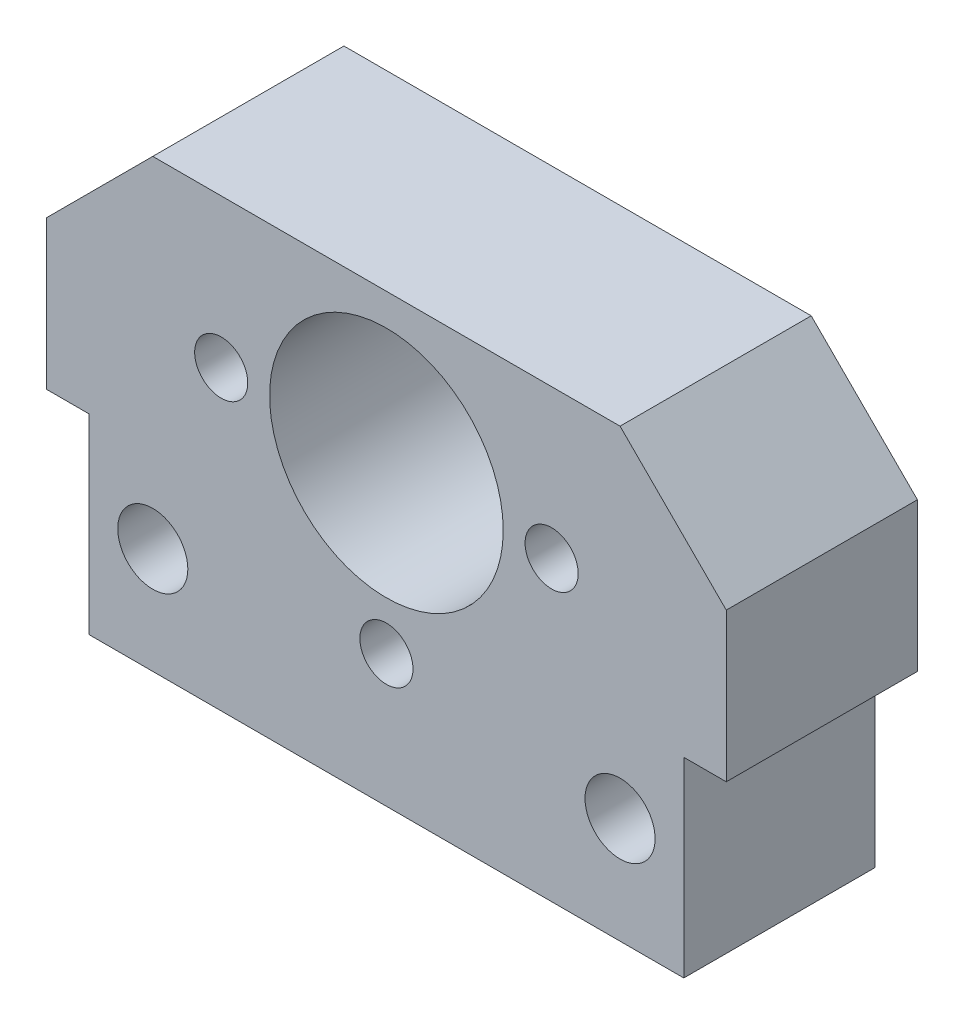
SolidWorks part; units mm, degrees
ref_plane "Plan de face" through (0, 0, 0) normal (0, 0, 1) x (1, 0, 0)
ref_plane "Plan de dessus" through (0, 0, 0) normal (0, 1, 0) x (1, 0, 0)
ref_plane "Plan de droite" through (0, 0, 0) normal (1, 0, 0) x (0, 0, -1)
sketch "Esquisse1" plane through (0, 0, 0) normal (0, 0, 1) x (1, 0, 0)
  line L1 (0, 0) -> (32, 0)
  line L2 (0, 0) -> (0, 19)
  line L3 (0, 19) -> (32, 19)
  line L4 (32, 0) -> (32, 19)
  dimension "D1" = 32
  dimension "D2" = 19
extrude "Boss.-Extru.1" add sketch "Esquisse1" along normal blind 9
sketch "Esquisse2" plane through (0, 0, 9) normal (0, 0, 1) x (1, 0, 0)
  line L0 (16, 12) -> (16, 19) construction
  line L1 (32, 19) -> (0, 19) construction
  line L2 (16, 12) -> (8.2218, 12) construction
  line L3 (16, 4.2218) -> (8.2218, 12) construction
  line L4 (16, 4.2218) -> (23.7782, 12) construction
  line L5 (16, 4.2218) -> (16, 12) construction
  line L6 (0, 0) -> (32, 0) construction
  line L7 (5, 0) -> (5, 3) construction
  circle A0 centre (16, 12) radius 5.5
  circle A1 centre (8.2218, 12) radius 1.25
  circle A2 centre (23.7782, 12) radius 1.25
  circle A3 centre (16, 4.2218) radius 1.25
  circle A4 centre (5, 3) radius 1.65
  circle A5 centre (27, 3) radius 1.65
  dimension "D1" = 11
  dimension "D3" = 2.5
  dimension "D5" = 3.3
  dimension "D2" = 12
  dimension "D7" = 9
  dimension "D4" = 11
  dimension "D6" = 11
extrude "Enlèv. mat.-Extru.1" cut sketch "Esquisse2" against normal through all
sketch "Esquisse3" plane through (0, 0, 9) normal (0, 0, 1) x (1, 0, 0)
  line L0 (16, 0) -> (16, 11.6118) construction
  line L1 (0, 0) -> (2, 0)
  line L2 (0, 0) -> (0, 7)
  line L3 (0, 7) -> (2, 7)
  line L4 (2, 0) -> (2, 7)
  line L5 (0, 0) -> (32, 0) construction
  line L6 (30, 0) -> (30, 7)
  line L7 (32, 7) -> (30, 7)
  line L8 (32, 0) -> (32, 7)
  line L9 (32, 0) -> (30, 0)
  dimension "D1" = 2
  dimension "D2" = 7
extrude "Enlèv. mat.-Extru.2" cut sketch "Esquisse3" against normal through all
sketch "Esquisse4" plane through (0, 0, 9) normal (0, 0, 1) x (1, 0, 0)
  line L0 (30, 7) -> (30, 0) construction
  line L1 (2, 0) -> (30, 0)
  line L2 (2, 0) -> (2, -2)
  line L3 (2, -2) -> (30, -2)
  line L4 (30, 0) -> (30, -2)
  dimension "D1" = 2
extrude "Boss.-Extru.2" add sketch "Esquisse4" against normal up to vertex (9 mm away)
chamfer "Chanfrein1" distance 5 angle 45 2 edges at (0, 19, 4.5) (32, 19, 4.5)
